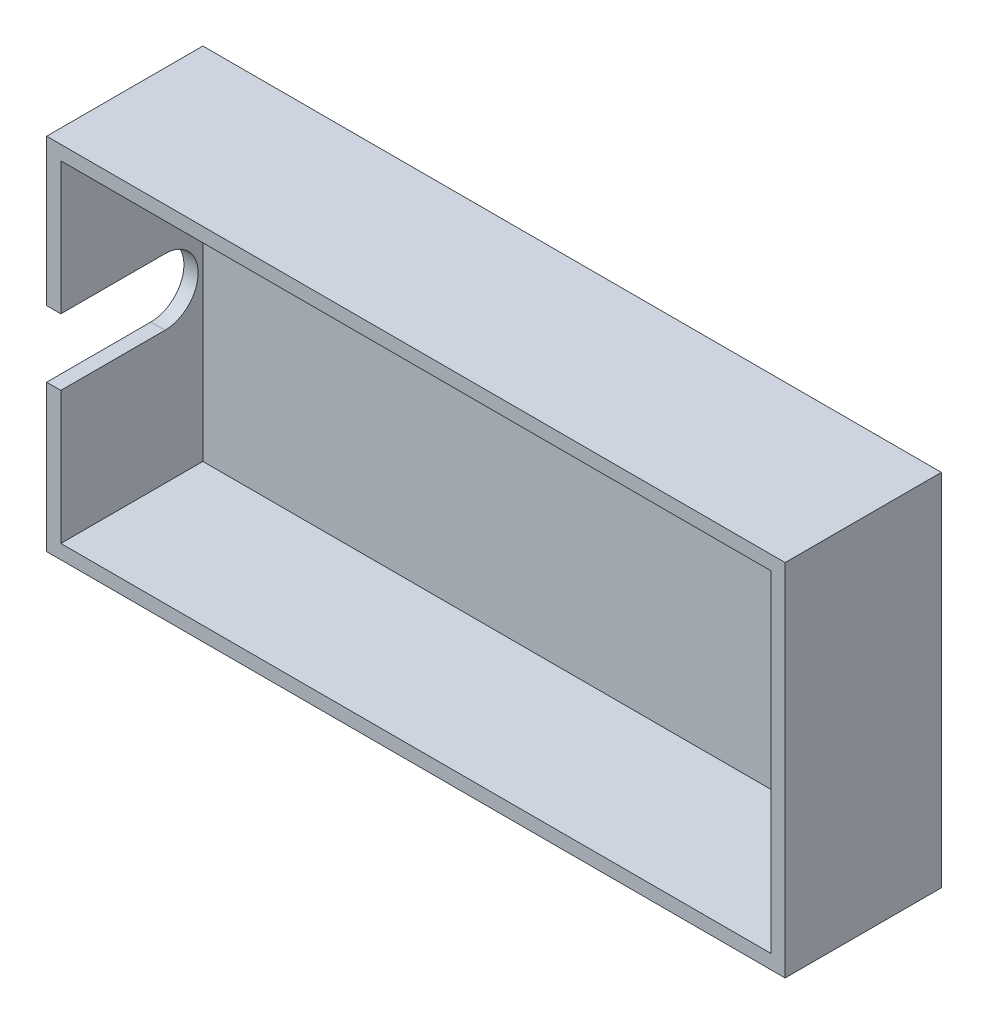
SolidWorks part; units mm, degrees
ref_plane "Plan de face" through (0, 0, 0) normal (0, 0, 1) x (1, 0, 0)
ref_plane "Plan de dessus" through (0, 0, 0) normal (0, 1, 0) x (1, 0, 0)
ref_plane "Plan de droite" through (0, 0, 0) normal (1, 0, 0) x (0, 0, -1)
sketch "Esquisse1" plane through (0, 0, 0) normal (0, 0, 1) x (1, 0, 0)
  line L1 (0, 35) -> (75, 35)
  line L2 (0, 35) -> (0, 0)
  line L3 (0, 0) -> (75, 0)
  line L4 (75, 35) -> (75, 0)
  point P4 (0, 0)
  dimension "D1" = 75
  dimension "D2" = 35
extrude "Boss.-Extru.1" add sketch "Esquisse1" along normal blind 15
shell "Coque1" thickness 1.5
sketch "Esquisse2" plane through (-1.5, 0, 0) normal (-1, 0, 0) x (0, 0, 1)
  line L0 (4, 17.5) -> (15.5029, 17.5) construction
  line L1 (4, 21) -> (15.5029, 21)
  line L2 (4, 14) -> (15.5029, 14)
  line L3 (-1.5, 36.5) -> (-1.5, -1.5) construction
  line L4 (15, 36.5) -> (15, -1.5) construction
  arc A0 (4, 21) -> (4, 14) centre (4, 17.5) ccw
  arc A1 (15.5029, 14) -> (15.5029, 21) centre (15.5029, 17.5) ccw
  point P2 (9.7515, 17.5)
  point P9 (0.5, 17.5)
  point P12 (15, 17.5)
  dimension "D2" = 3.5
  dimension "D1" = 5.5
extrude "Enlèv. mat.-Extru.1" cut sketch "Esquisse2" against normal blind 15
